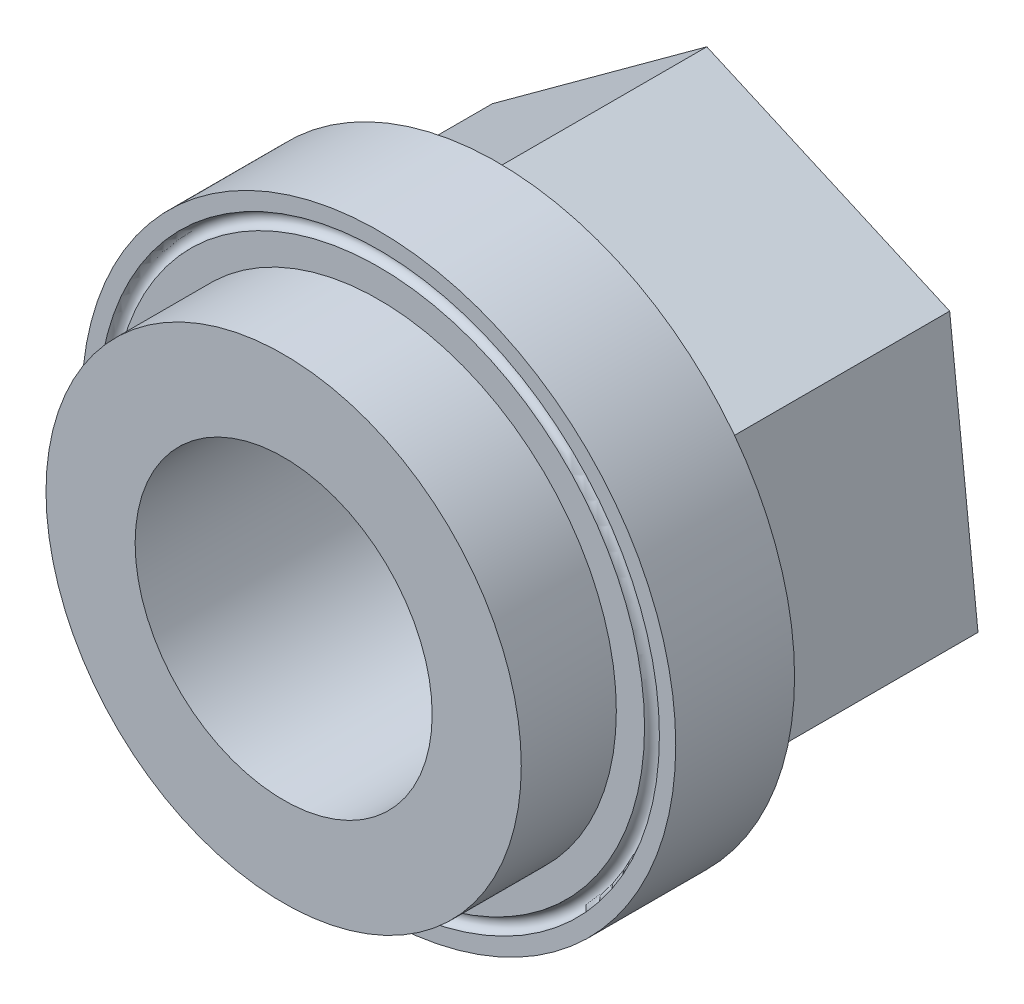
SolidWorks part; units mm, degrees
material "AISI 316 Annealed Stainless Steel Bar (SS)"
ref_plane "Front Plane" through (0, 0, 0) normal (0, 0, 1) x (1, 0, 0)
ref_plane "Top Plane" through (0, 0, 0) normal (0, 1, 0) x (1, 0, 0)
ref_plane "Right Plane" through (0, 0, 0) normal (1, 0, 0) x (0, 0, -1)
sketch "Sketch2" plane through (0, 0, 0) normal (0, 0, 1) x (1, 0, 0)
  circle A0 centre (0, 0) radius 25
  dimension "D1" = 50
extrude "Boss-Extrude1" add sketch "Sketch2" along normal blind 10
sketch "Sketch3" plane through (0, 0, 10) normal (0, 0, 1) x (1, 0, 0)
  circle A0 centre (0, 0) radius 20
  dimension "D1" = 40
extrude "Boss-Extrude2" add sketch "Sketch3" along normal blind 8 contours A0
cosmetic thread "Cosmetic Thread1" parameters "D2"=27.4295
cosmetic thread "Cosmetic Thread3" parameters "D2"=27.4295
sketch "Sketch4" plane through (0, 0, 0) normal (0, 0, -1) x (-1, 0, 0)
  line L1 (-20.4371, -9.047) -> (-2.3836, -22.2226)
  line L2 (-2.3836, -22.2226) -> (18.0535, -13.1756)
  line L3 (18.0535, -13.1756) -> (20.4371, 9.047)
  line L4 (20.4371, 9.047) -> (2.3836, 22.2226)
  line L5 (2.3836, 22.2226) -> (-18.0535, 13.1756)
  line L6 (-18.0535, 13.1756) -> (-20.4371, -9.047)
  circle A0 centre (0, 0) radius 19.3557 construction
extrude "Boss-Extrude3" add sketch "Sketch4" along normal blind 20
sketch "Sketch5" plane through (0, 0, -20) normal (0, 0, -1) x (-1, 0, 0)
  circle A0 centre (0, 0) radius 12.5
  dimension "D1" = 25
extrude "Cut-Extrude1" cut sketch "Sketch5" against normal through all
cosmetic thread "Cosmetic Thread2" parameters "D1"=20, "D2"=28.575
sketch "Sketch6" plane through (0, 0, 10) normal (0, 0, 1) x (1, 0, 0)
  circle A0 centre (0, 0) radius 23
  dimension "D1" = 46
sweep "Cut-Sweep1" cut path "Sketch6" circular profile diameter 1.25 parameters "D3"=1.25
